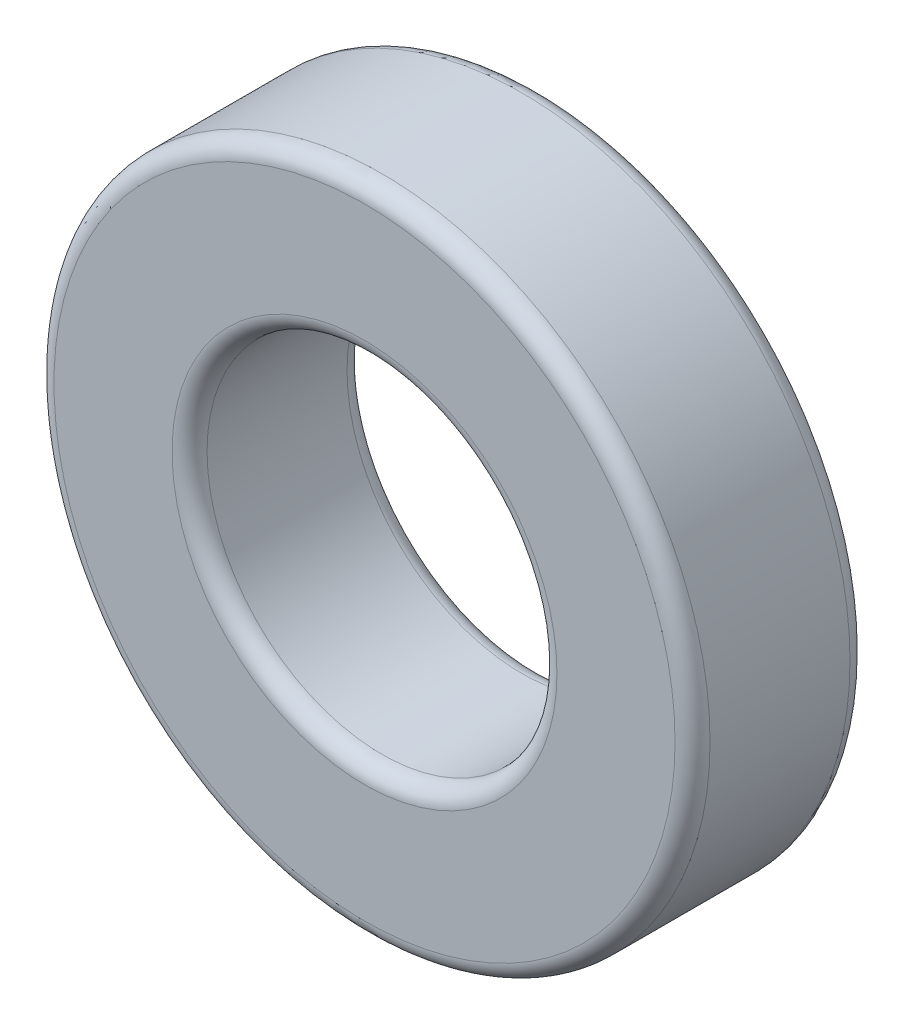
SolidWorks part; units mm, degrees
material "ABS PC"
ref_plane "Front Plane" through (0, 0, 0) normal (0, 0, 1) x (1, 0, 0)
ref_plane "Top Plane" through (0, 0, 0) normal (0, 1, 0) x (1, 0, 0)
ref_plane "Right Plane" through (0, 0, 0) normal (1, 0, 0) x (0, 0, -1)
sketch "Sketch1" plane through (0, 0, 0) normal (0, 0, 1) x (1, 0, 0)
  circle A0 centre (0, 0) radius 0.5
  circle A1 centre (0, 0) radius 0.9375
  dimension "D1" = 1
  dimension "D2" = 1.875
extrude "Boss-Extrude1" add sketch "Sketch1" along normal blind 0.5
fillet "Fillet1" radius 0.05 4 edges at (0.9375, 0, 0) (0.9375, 0, 0.5) (0.5, 0, 0) (0.5, 0, 0.5)
